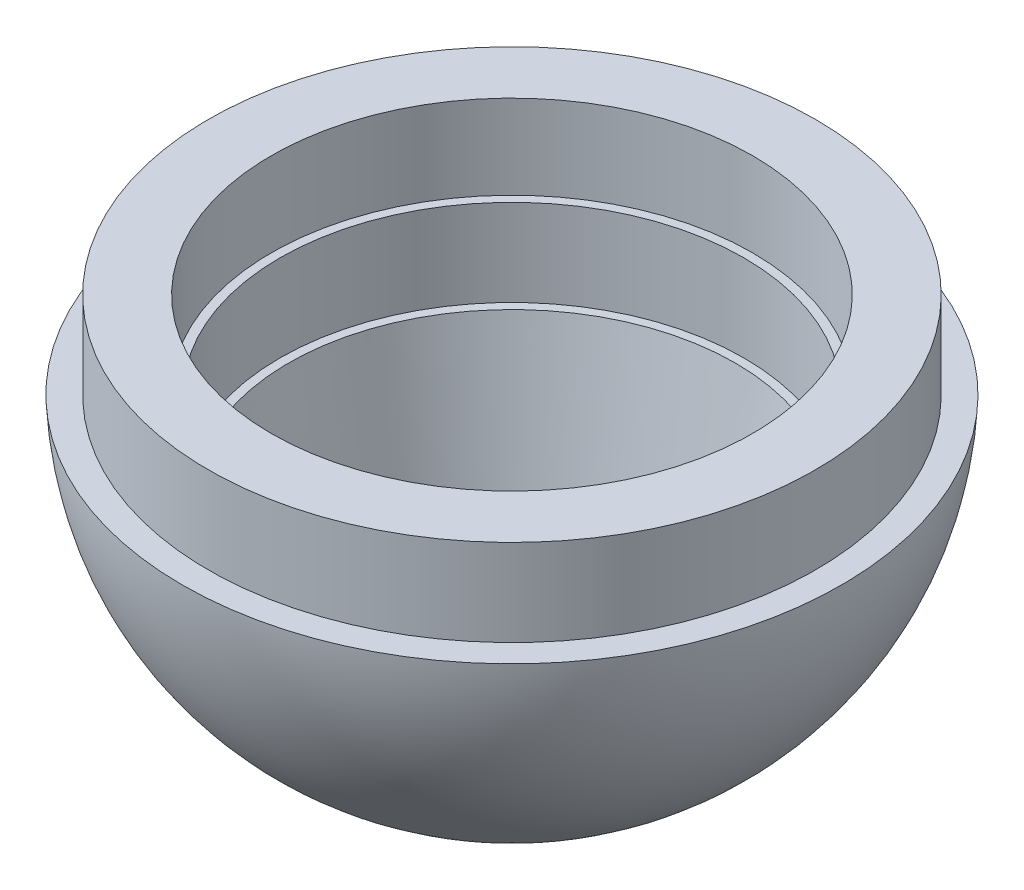
SolidWorks part; units mm, degrees
ref_plane "Front Plane" through (0, 0, 0) normal (0, 0, 1) x (1, 0, 0)
ref_plane "Top Plane" through (0, 0, 0) normal (0, 1, 0) x (1, 0, 0)
ref_plane "Right Plane" through (0, 0, 0) normal (1, 0, 0) x (0, 0, -1)
sketch "Sketch1" plane through (0, 0, 0) normal (1, 0, 0) x (0, 0, -1)
  line L0 (0, 0) -> (0, 30.955) construction
  line L1 (-27.75, 0) -> (-27.75, -1.5)
  line L2 (-27.75, -1.5) -> (-26.75, -1.5)
  line L3 (-26.75, -1.5) -> (-26.75, -11.5)
  line L4 (-26.75, -11.5) -> (-25.75, -11.5)
  line L5 (0, 0) -> (-17.3092, 0) construction
  line L6 (-20.8274, -29.9) -> (0, -29.9)
  line L7 (-25.75, -11.5) -> (-22.797, -28.2473)
  line L8 (-19.9369, -32.4) -> (0, -32.4)
  line L9 (0, -32.4) -> (0, -29.9)
  line L10 (-27.75, 0) -> (-27.75, 8.2)
  line L11 (-27.75, 8.2) -> (-35, 8.2)
  line L12 (-35, 8.2) -> (-35, -1.8)
  line L13 (-35, -1.8) -> (-38, -1.8)
  arc A0 (-19.9369, -32.4) -> (-38, -1.8) centre (0, 0) cw
  arc A1 (-20.8274, -29.9) -> (-22.797, -28.2473) centre (-20.8274, -27.9) cw
  arc A2 (-19.9369, -32.4) -> (0, -38.0426) centre (0, 0) ccw construction
  point P16 (0, 0)
  point P21 (0, 0)
  dimension "D10" = 2
  dimension "D14" = 38.0426
  dimension "D1" = 55.5
  dimension "D2" = 1
  dimension "D3" = 10
  dimension "D4" = 10
  dimension "D5" = 18.4
  dimension "D6" = 1.5
  dimension "D7" = 8.2
  dimension "D8" = 35
  dimension "D9" = 2.5
  dimension "D11" = 10
  dimension "D12" = 3
  dimension "D13" = 1
revolve "Revolve1" add sketch "Sketch1" angle 360 about L0
